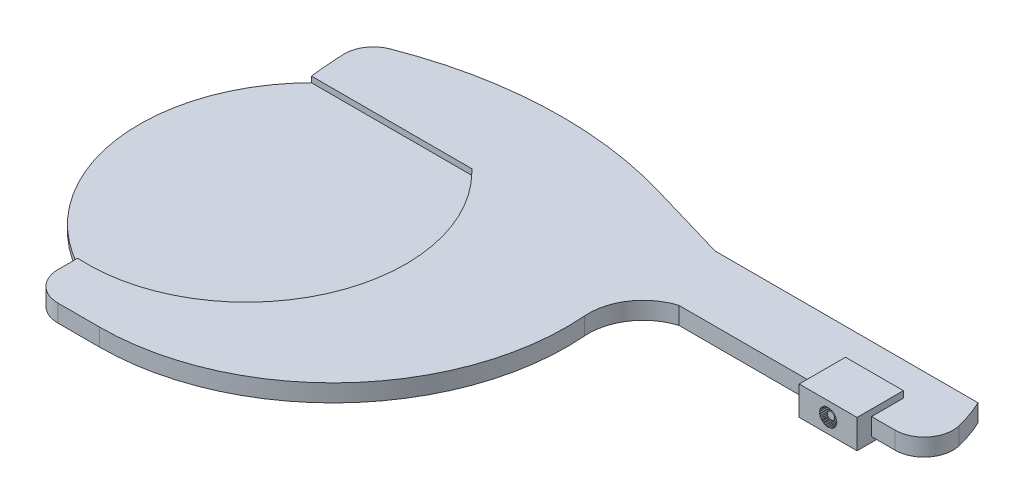
SolidWorks part; units mm, degrees
ref_plane "Front Plane" through (0, 0, 0) normal (0, 0, 1) x (1, 0, 0)
ref_plane "Top Plane" through (0, 0, 0) normal (0, 1, 0) x (1, 0, 0)
ref_plane "Right Plane" through (0, 0, 0) normal (1, 0, 0) x (0, 0, -1)
sketch "Sketch2" plane through (0, 0, 0) normal (0, 1, 0) x (1, 0, 0)
  circle A0 centre (0, 0) radius 30
  dimension "D1" = 60
extrude "Boss-Extrude1" add sketch "Sketch2" along normal blind 1
sketch "Sketch3" plane through (0, 1, 0) normal (0, 1, 0) x (1, 0, 0)
  line L0 (-14.2905, -26.3777) -> (-14.2905, -34.7827)
  line L1 (-14.2905, -34.7827) -> (-2.1106, -34.7827)
  line L2 (44.6841, 18.5111) -> (87.6417, 18.5111)
  line L3 (85.0987, 29.7674) -> (39.6742, 29.7674)
  line L4 (39.6742, 29.7674) -> (25.7141, 33.8567)
  line L5 (-21.3555, 21.0699) -> (6.3602, 21.0699)
  line L6 (6.3602, 21.0699) -> (6.8673, 20.5632)
  arc A0 (-2.1106, -34.7827) -> (38.1175, 8.7735) centre (-2.1106, 5.5725) ccw
  arc A1 (38.1175, 8.7735) -> (44.6841, 18.5111) centre (47.5122, 9.521) cw
  arc A2 (87.6417, 18.5111) -> (85.0987, 29.7674) centre (61.4573, 18.5111) ccw
  arc A3 (25.7141, 33.8567) -> (-21.8993, 30.5423) centre (6.3853, -32.1279) ccw
  arc A4 (-21.8993, 30.5423) -> (-21.3555, 21.0699) centre (60.6406, 30.5285) ccw
  circle A5 centre (0, 0) radius 30 construction
  arc A6 (6.8673, 20.5632) -> (-14.2905, -26.3777) centre (-12.5867, 1.0931) cw
extrude "Boss-Extrude2" add sketch "Sketch3" along normal blind 1 and the other way blind 2
scale "Scale1" scale about centroid uniform scaling yes scale factor 2
sketch "Sketch5" plane through (0, 0, -29.457) normal (0, 0, 1) x (1, 0, 0)
  line L1 (117.1364, -4.2508) -> (137.1364, -4.2508)
  line L2 (117.1364, -4.2508) -> (117.1364, 5.7492)
  line L3 (117.1364, 5.7492) -> (137.1364, 5.7492)
  line L4 (137.1364, -4.2508) -> (137.1364, 5.7492)
  line L5 (117.1364, -4.2508) -> (137.1364, 5.7492) construction
  line L6 (117.1364, 5.7492) -> (137.1364, -4.2508) construction
  point P0 (127.1364, 0.7492)
  dimension "D1" = 20
  dimension "D2" = 10
extrude "Boss-Extrude3" add sketch "Sketch5" along normal blind 5 and the other way blind 11
fillet "Fillet1" radius 10 1 edges at (-47.3766, 0.5, 77.1307)
fillet "Fillet2" radius 10 1 edges at (-62.5943, 0.5, -53.5194)
fillet "Fillet3" radius 10 1 edges at (156.4876, 0.5, -29.457)
sketch "Sketch12" plane through (0, 0, -24.457) normal (0, 0, 1) x (1, 0, 0)
  line L75 (127.1364, 5.7492) -> (127.1364, -4.2508) construction
  line L78 (137.1364, 5.7492) -> (117.1364, 5.7492) construction
  line L80 (117.1364, -4.2508) -> (137.1364, -4.2508) construction
  line L81 (117.1364, 0.7492) -> (137.1364, 0.7492) construction
  line L82 (137.1364, -4.2508) -> (137.1364, 5.7492) construction
  line L83 (124.4364, 0.7492) -> (124.1455, 0.9612)
  line L84 (124.1455, 0.9612) -> (124.1867, 1.2876)
  line L85 (124.1867, 1.2876) -> (124.5212, 1.4206)
  line L86 (124.5212, 1.4206) -> (124.2922, 1.6983)
  line L87 (124.2922, 1.6983) -> (124.4133, 2.0042)
  line L88 (124.4133, 2.0042) -> (124.7704, 2.0499)
  line L89 (124.7704, 2.0499) -> (124.6176, 2.3759)
  line L90 (124.6176, 2.3759) -> (124.811, 2.642)
  line L91 (124.811, 2.642) -> (125.1682, 2.5974)
  line L92 (125.1682, 2.5974) -> (125.1013, 2.9512)
  line L93 (125.1013, 2.9512) -> (125.3548, 3.1609)
  line L94 (125.3548, 3.1609) -> (125.6897, 3.0288)
  line L95 (125.6897, 3.0288) -> (125.7128, 3.3881)
  line L96 (125.7128, 3.3881) -> (126.0105, 3.5282)
  line L97 (126.0105, 3.5282) -> (126.3021, 3.317)
  line L98 (126.3021, 3.317) -> (126.4138, 3.6592)
  line L99 (126.4138, 3.6592) -> (126.737, 3.7209)
  line L100 (126.737, 3.7209) -> (126.9669, 3.4438)
  line L101 (126.9669, 3.4438) -> (127.1602, 3.7475)
  line L102 (127.1602, 3.7475) -> (127.4886, 3.7268)
  line L103 (127.4886, 3.7268) -> (127.6423, 3.4013)
  line L104 (127.6423, 3.4013) -> (127.9051, 3.6474)
  line L105 (127.9051, 3.6474) -> (128.218, 3.5457)
  line L106 (128.218, 3.5457) -> (128.286, 3.1922)
  line L107 (128.286, 3.1922) -> (128.6017, 3.3652)
  line L108 (128.6017, 3.3652) -> (128.8795, 3.1889)
  line L109 (128.8795, 3.1889) -> (128.8575, 2.8295)
  line L110 (128.8575, 2.8295) -> (129.2063, 2.9186)
  line L111 (129.2063, 2.9186) -> (129.4315, 2.6787)
  line L112 (129.4315, 2.6787) -> (129.3208, 2.3362)
  line L113 (129.3208, 2.3362) -> (129.6808, 2.3356)
  line L114 (129.6808, 2.3356) -> (129.8393, 2.0473)
  line L115 (129.8393, 2.0473) -> (129.6468, 1.7431)
  line L116 (129.6468, 1.7431) -> (129.9954, 1.6531)
  line L117 (129.9954, 1.6531) -> (130.0772, 1.3344)
  line L118 (130.0772, 1.3344) -> (129.8151, 1.0876)
  line L119 (129.8151, 1.0876) -> (130.1303, 0.9137)
  line L120 (130.1303, 0.9137) -> (130.1303, 0.5847)
  line L121 (130.1303, 0.5847) -> (129.8151, 0.4108)
  line L122 (129.8151, 0.4108) -> (130.0772, 0.1639)
  line L123 (130.0772, 0.1639) -> (129.9954, -0.1547)
  line L124 (129.9954, -0.1547) -> (129.6468, -0.2448)
  line L125 (129.6468, -0.2448) -> (129.8393, -0.549)
  line L126 (129.8393, -0.549) -> (129.6808, -0.8373)
  line L127 (129.6808, -0.8373) -> (129.3208, -0.8379)
  line L128 (129.3208, -0.8379) -> (129.4315, -1.1804)
  line L129 (129.4315, -1.1804) -> (129.2063, -1.4202)
  line L130 (129.2063, -1.4202) -> (128.8575, -1.3312)
  line L131 (128.8575, -1.3312) -> (128.8795, -1.6905)
  line L132 (128.8795, -1.6905) -> (128.6017, -1.8668)
  line L133 (128.6017, -1.8668) -> (128.286, -1.6939)
  line L134 (128.286, -1.6939) -> (128.218, -2.0474)
  line L135 (128.218, -2.0474) -> (127.9051, -2.1491)
  line L136 (127.9051, -2.1491) -> (127.6423, -1.903)
  line L137 (127.6423, -1.903) -> (127.4886, -2.2285)
  line L138 (127.4886, -2.2285) -> (127.1364, -2.2508)
  line L139 (127.1364, -2.2508) -> (126.9669, -1.9455)
  line L140 (126.9669, -1.9455) -> (126.737, -2.2226)
  line L141 (126.737, -2.2226) -> (126.3799, -2.1539)
  line L142 (126.3799, -2.1539) -> (126.3021, -1.8187)
  line L143 (126.3021, -1.8187) -> (126.0105, -2.0299)
  line L144 (126.0105, -2.0299) -> (125.7128, -1.8898)
  line L145 (125.7128, -1.8898) -> (125.6897, -1.5305)
  line L146 (125.6897, -1.5305) -> (125.3548, -1.6626)
  line L147 (125.3548, -1.6626) -> (125.1013, -1.4528)
  line L148 (125.1013, -1.4528) -> (125.1682, -1.0991)
  line L149 (125.1682, -1.0991) -> (124.811, -1.1437)
  line L150 (124.811, -1.1437) -> (124.6176, -0.8775)
  line L151 (124.6176, -0.8775) -> (124.7704, -0.5516)
  line L152 (124.7704, -0.5516) -> (124.4133, -0.5059)
  line L153 (124.4133, -0.5059) -> (124.2922, -0.2)
  line L154 (124.2922, -0.2) -> (124.5212, 0.0777)
  line L155 (124.5212, 0.0777) -> (124.1867, 0.2107)
  line L156 (124.1867, 0.2107) -> (124.1455, 0.5371)
  line L157 (124.1455, 0.5371) -> (124.4364, 0.7492)
  circle A0 centre (127.1364, 0.7492) radius 2.7 construction
  point P11 (127.1364, 0.7492)
extrude "Cut-Extrude3" cut sketch "Sketch12" against normal blind 3
sketch "Sketch13" plane through (0, 0, -27.457) normal (0, 0, 1) x (1, 0, 0)
  line L0 (127.1364, 5.7492) -> (127.1364, -4.2508) construction
  line L1 (137.1364, 5.7492) -> (117.1364, 5.7492) construction
  line L2 (117.1364, -4.2508) -> (137.1364, -4.2508) construction
  line L3 (117.1364, 0.7492) -> (137.1364, 0.7492) construction
  line L4 (137.1364, -4.2508) -> (137.1364, 5.7492) construction
  circle A0 centre (127.1364, 0.7492) radius 1.25
  point P11 (127.1364, 0.7492)
  dimension "D1" = 2.5
extrude "Boss-Extrude4" add sketch "Sketch13" along normal blind 2
scale "Scale2" scale about centroid uniform scaling yes scale factor 0.8
